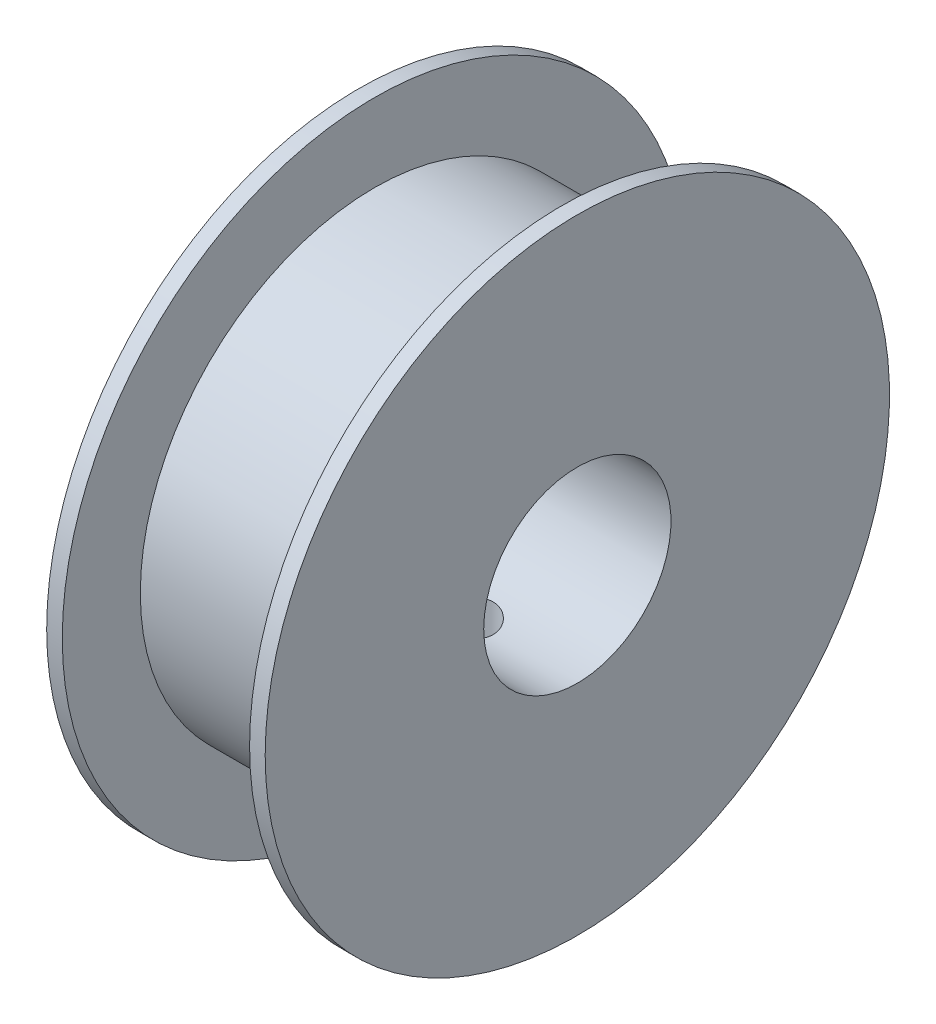
SolidWorks part; units mm, degrees
material "6061 合金"
ref_plane "正面" through (0, 0, 0) normal (0, 0, 1) x (1, 0, 0)
ref_plane "平面" through (0, 0, 0) normal (0, 1, 0) x (1, 0, 0)
ref_plane "右側面" through (0, 0, 0) normal (1, 0, 0) x (0, 0, -1)
sketch "ｽｹｯﾁ2" plane through (0, 0, 0) normal (0, 1, 0) x (1, 0, 0)
  line L0 (-44.7309, -0.056) -> (-44.7309, -14.056)
  line L1 (-44.7309, -0.056) -> (-43.7309, -0.056)
  line L2 (-43.7309, -0.056) -> (-43.7309, -5.056)
  line L3 (-43.7309, -5.056) -> (-31.7309, -5.056)
  line L4 (-31.7309, -5.056) -> (-31.7309, -0.056)
  line L5 (-31.7309, -0.056) -> (-30.7309, -0.056)
  line L6 (-30.7309, -0.056) -> (-30.7309, -14.056)
  line L7 (-30.7309, -14.056) -> (-44.7309, -14.056)
  line L8 (-49.8494, -20.056) -> (-18.0543, -20.056) construction
  dimension "D1" = 1
  dimension "D2" = 1
  dimension "D3" = 5
  dimension "D4" = 5
  dimension "D5" = 20
  dimension "D6" = 14
  dimension "D7" = 6
revolve "回転1" add sketch "ｽｹｯﾁ2" angle 360 about L8
sketch "ｽｹｯﾁ3" plane through (0, 0, 0) normal (0, 1, 0) x (1, 0, 0)
  line L1 (-43.7309, -0.056) -> (-44.7309, -0.056) construction
  line L2 (-30.7309, -40.056) -> (-30.7309, -0.056) construction
  circle A0 centre (-37.7309, -20.056) radius 1.6
  dimension "D1" = 3.2
  dimension "D2" = 20
  dimension "D3" = 7
extrude "ｶｯﾄ - 押し出し1" cut sketch "ｽｹｯﾁ3" against normal through all
